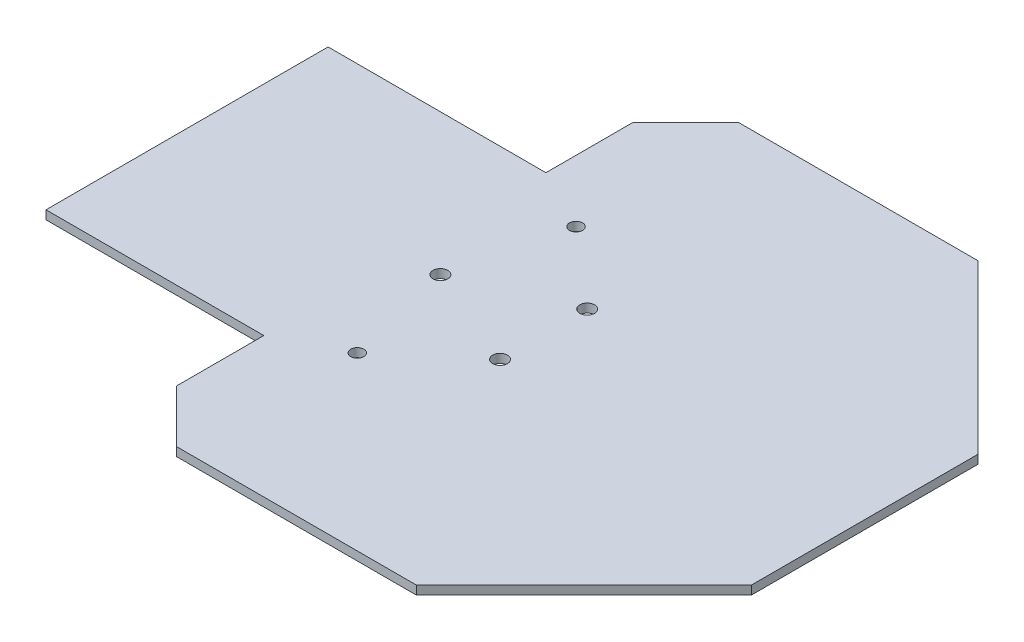
SolidWorks part; units mm, degrees
ref_plane "Front Plane" through (0, 0, 0) normal (0, 0, 1) x (1, 0, 0)
ref_plane "Top Plane" through (0, 0, 0) normal (0, 1, 0) x (1, 0, 0)
ref_plane "Right Plane" through (0, 0, 0) normal (1, 0, 0) x (0, 0, -1)
sketch "Sketch1" plane through (0, 0, 0) normal (0, 1, 0) x (1, 0, 0)
  line L0 (0, 12.09) -> (0, 116.84)
  line L5 (12.09, 128.93) -> (67.09, 128.93)
  line L6 (67.09, 128.93) -> (105.555, 90.46)
  line L10 (105.555, 38.46) -> (67.09, 0)
  line L11 (67.09, 0) -> (12.09, 0)
  line L12 (0, 116.84) -> (12.09, 128.93)
  line L13 (12.09, 0) -> (0, 12.09)
  line L14 (105.555, 90.46) -> (105.555, 38.46)
  point P0 (0, 0)
  point P1 (0, 128.93)
  dimension "D1" = 104.75
  dimension "D2" = 52
  dimension "D3" = 55
  dimension "D6" = 38.47
extrude "Boss-Extrude1" add sketch "Sketch1" along normal blind 2
sketch "Sketch2" plane through (0, 2, 0) normal (0, 1, 0) x (1, 0, 0)
  circle A6 centre (8.15, 64.465) radius 1.7 construction
  circle A7 centre (31.85, 54.465) radius 1.7 construction
  circle A8 centre (31.85, 74.465) radius 1.7 construction
  circle A9 centre (8.15, 64.465) radius 1.7
  circle A10 centre (31.85, 54.465) radius 1.7
  circle A11 centre (31.85, 74.465) radius 1.7
extrude "Cut-Extrude1" cut sketch "Sketch2" against normal through all
sketch "Sketch7" plane through (0, 2, 0) normal (0, 1, 0) x (1, 0, 0)
  line L0 (12.09, 128.93) -> (12.09, 89.57) construction
  line L1 (12.09, 89.57) -> (14.18, 89.57) construction
  line L2 (105.555, 64.46) -> (0, 64.465) construction
  line L3 (105.555, 38.46) -> (105.555, 90.46) construction
  line L4 (0, 116.84) -> (0, 12.09) construction
  circle A0 centre (14.18, 89.57) radius 1.5
  circle A1 centre (14.1776, 39.3587) radius 1.5
  dimension "D3" = 3
  dimension "D1" = 39.36
  dimension "D2" = 2.09
extrude "Cut-Extrude2" cut sketch "Sketch7" against normal up to next
sketch "Sketch10" plane through (0, 0, 0) normal (-1, 0, 0) x (0, 0, 1)
  line L0 (-116.84, 0) -> (-12.09, 0) construction
  line L1 (-96.84, 2) -> (-32.09, 2)
  line L2 (-96.84, 2) -> (-96.84, 0)
  line L3 (-96.84, 0) -> (-32.09, 0)
  line L4 (-32.09, 2) -> (-32.09, 0)
  line L5 (-116.84, 2) -> (-116.84, 0) construction
  line L6 (-12.09, 2) -> (-12.09, 0) construction
  line L7 (-116.84, 2) -> (-12.09, 2) construction
  dimension "D1" = 20
  dimension "D2" = 20
extrude "Boss-Extrude3" add sketch "Sketch10" along normal blind 50
